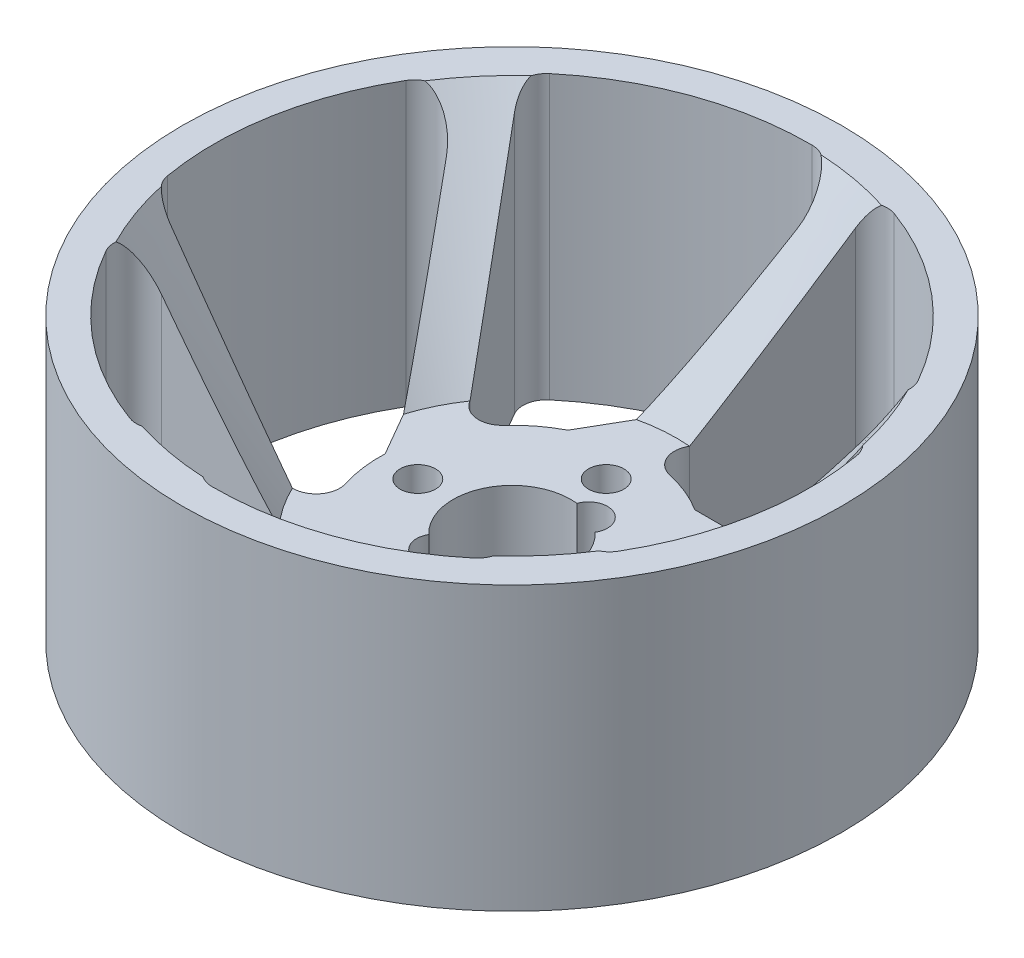
SolidWorks part; units mm, degrees
ref_plane "Front Plane" through (0, 0, 0) normal (0, 0, 1) x (1, 0, 0)
ref_plane "Top Plane" through (0, 0, 0) normal (0, 1, 0) x (1, 0, 0)
ref_plane "Right Plane" through (0, 0, 0) normal (1, 0, 0) x (0, 0, -1)
sketch "Sketch1" plane through (0, 0, 0) normal (0, 1, 0) x (1, 0, 0)
  circle A0 centre (0, 0) radius 28
  dimension "D1" = 56
extrude "Boss-Extrude1" add sketch "Sketch1" along normal blind 24
sketch "Sketch3" plane through (0, 0, 0) normal (0, 1, 0) x (1, 0, 0)
  line L0 (5.4848, 9.5) -> (23.4487, 9.5)
  line L1 (3.4641, 6) -> (-3.4641, 6) construction
  line L2 (-3.4641, 6) -> (-6.9282, 0) construction
  line L4 (-6.9282, 0) -> (-3.4641, -6) construction
  line L5 (-3.4641, -6) -> (3.4641, -6) construction
  line L6 (3.4641, -6) -> (6.9282, 0) construction
  line L7 (6.9282, 0) -> (3.4641, 6) construction
  line L9 (-6.9282, 0) -> (7.093, 24.2854)
  line L11 (5.4848, 9.5) -> (-5.4848, 9.5) construction
  line L12 (-5.4848, 9.5) -> (-10.9697, 0) construction
  line L13 (-10.9697, 0) -> (-5.4848, -9.5) construction
  line L14 (-5.4848, -9.5) -> (5.4848, -9.5) construction
  line L15 (5.4848, -9.5) -> (10.9697, 0) construction
  line L16 (10.9697, 0) -> (5.4848, 9.5) construction
  circle A0 centre (0, 0) radius 25.3
  circle A10 centre (0, 0) radius 6 construction
  circle A11 centre (0, 0) radius 9.5 construction
  circle A12 centre (0, 0) radius 28 construction
  circle A22 centre (0, 0) radius 28 construction
  arc A23 (8.7007, 23.7568) -> (6.2809, 22.8788) centre (8.0129, 21.8788) ccw
  arc A28 (20.2643, 9.5) -> (22.0037, 12.4871) centre (20.2643, 11.5) ccw
  circle A29 centre (0, 0) radius 11.25
  arc A30 (1.1198, 13.9395) -> (2.4213, 10.9863) centre (2.8518, 12.9395) ccw
  dimension "D2" = 3.5
  dimension "D3" = 12
  dimension "D4" = 2.7
  dimension "D5" = 4
  dimension "D6" = 22.5
sketch "Sketch6" plane through (0, 0, 0) normal (0, 1, 0) x (1, 0, 0)
  circle A0 centre (0, 0) radius 1.9
  dimension "D1" = 3.8
extrude "Cut-Extrude6" cut sketch "Sketch6" along normal up to surface (24 mm away) up to face at (0, 24, 28)
ref_plane "Plane1" through (0, 12, 0) normal (0, 1, 0) x (1, 0, 0)
extrude "Cut-Extrude7" cut sketch "Sketch3" along normal up to surface (24 mm away)
pattern_circular "CirPattern1" count 6 over 360 about axis through (0, 0, 0) along (0, 1, 0) of "Cut-Extrude7"
sketch "Sketch8" plane through (0, 12, 0) normal (0, 1, 0) x (1, 0, 0)
  line L0 (0, 0) -> (0, -28) construction
  line L5 (-4.4539, -25.6157) -> (4.4539, -25.6157)
  line L6 (-2.5, -29) -> (2.5, -29)
  line L7 (4.4539, -25.6157) -> (2.5, -29)
  line L8 (-4.4539, -25.6157) -> (-2.5, -29)
  circle A7 centre (0, 0) radius 26 construction
  circle A8 centre (0, 0) radius 28 construction
  point P10 (0, -25.6157)
  point P13 (0, -29)
  dimension "D1" = 2
  dimension "D2" = 1
  dimension "D3" = 60
  dimension "D4" = 5
sketch "Sketch13" plane through (0, 24, 0) normal (0, 1, 0) x (0.9417, 0, -0.3365)
  line L0 (0, 0) -> (0, -28) construction
  line L5 (-4.4539, -25.6157) -> (4.4539, -25.6157)
  line L6 (-2.5, -29) -> (2.5, -29)
  line L7 (4.4539, -25.6157) -> (2.5, -29)
  line L8 (-4.4539, -25.6157) -> (-2.5, -29)
  circle A7 centre (0, 0) radius 26 construction
  point P10 (0, -25.6157)
  point P13 (0, -29)
loft "Cut-Loft6" [suppressed] cut profiles "Sketch13", "Sketch8"
mirror "Mirror10" [suppressed] about plane through (0, 12, 0) normal (0, 1, 0)
pattern_circular "CirPattern6" [suppressed] count 6 over 360
sketch "Sketch14" plane through (0, 0, 0) normal (0, 0, 1) x (1, 0, 0)
  line L1 (28, 0) -> (28, 24) construction
  line L2 (25.5, 13) -> (25.5, 12)
  line L3 (30.8, 12) -> (-30.8, 12) construction
  line L4 (25.5, 12) -> (28, 12)
  line L5 (25.5, 13) -> (28, 14)
  line L6 (28, 14) -> (28, 12)
  dimension "D1" = 2.5
  dimension "D2" = 2
  dimension "D3" = 1
revolve "Revolve1" add sketch "Sketch14" angle 360 about axis through (0, 24, 0) along (0, -1, 0)
mirror "Mirror11" about plane through (0, 12, 0) normal (0, 1, 0) of "Revolve1"
sketch "Sketch15" plane through (0, 0, 0) normal (0, 0, 1) x (1, 0, 0)
  line L0 (5, 8) -> (5, 0)
  line L1 (5, 8) -> (14, 8)
  line L2 (-28, 0) -> (28, 0) construction
  line L3 (14, 8) -> (25, 24)
  line L4 (28, 24) -> (-28, 24) construction
  line L5 (25, 24) -> (0, 24)
  line L6 (0, 0) -> (0, 34.2011) construction
  line L7 (0, 24) -> (0, 0) construction
  line L8 (5, 0) -> (0, 0)
  line L9 (0, 8) -> (0, 0)
  line L10 (-1.1198, 24) -> (-6.2809, 24) construction
  line L14 (0, 8) -> (0, 0) construction
  line L16 (0, 24) -> (0, 0) construction
  line L19 (0, 8) -> (0, 24)
  dimension "D1" = 16
  dimension "D2" = 25
  dimension "D3" = 14
  dimension "D4" = 5
revolve "Cut-Revolve5" cut sketch "Sketch15" angle 360 about L14
sketch "Sketch16" plane through (0, 0, 0) normal (0, 1, 0) x (1, 0, 0)
  line L1 (0, 6.9398) -> (-6.01, 3.4699)
  line L2 (-6.01, 3.4699) -> (-6.01, -3.4699)
  line L3 (-6.01, -3.4699) -> (0, -6.9398)
  line L4 (0, -6.9398) -> (6.01, -3.4699)
  line L5 (6.01, -3.4699) -> (6.01, 3.4699)
  line L6 (6.01, 3.4699) -> (0, 6.9398)
  circle A0 centre (0, 0) radius 6.01 construction
  dimension "D1" = 12.02
extrude "Cut-Extrude8" [suppressed] cut sketch "Sketch16" along normal blind 9
sketch "Sketch17" plane through (0, 0, 0) normal (0, 1, 0) x (1, 0, 0)
  circle A0 centre (0, 0) radius 8 construction
  circle A1 centre (0, 8) radius 1.5
  circle A2 centre (8, 0) radius 1.5
  circle A3 centre (0, -8) radius 1.5
  circle A4 centre (-8, 0) radius 1.5
  point P14 (0, 0)
  dimension "D1" = 16
  dimension "D2" = 3
  dimension "D3" = 4
extrude "Cut-Extrude9" cut sketch "Sketch17" along normal up to surface (8 mm away) up to face at (0, 8, 5)
sketch "Sketch18" plane through (0, 0, 0) normal (0, 1, 0) x (1, 0, 0)
  line L0 (-2.0642, -4.4357) -> (2.0642, 4.4357) construction
  line L1 (-2.7424, -5.8931) -> (2.7424, 5.8931) construction
  circle A1 centre (2.0642, 4.4357) radius 1.6075
  circle A2 centre (-2.0642, -4.4357) radius 1.6075
  circle A3 centre (0, 0) radius 5 construction
  point P3 (0, 0)
  point P5 (0.548, 4.9699)
  point P6 (3.4493, 3.6197)
  point P8 (2.7424, 5.8931)
  point P11 (0, 0)
  dimension "D2" = 3.2
  dimension "D1" = 13
extrude "Cut-Extrude10" cut sketch "Sketch18" against normal up to surface (12 mm away)
